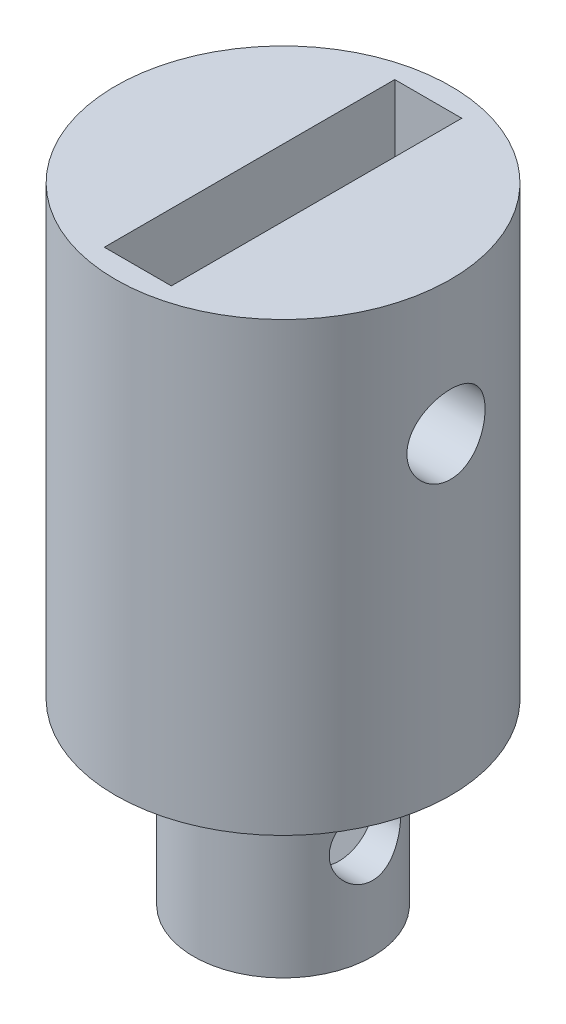
SolidWorks part; units mm, degrees
ref_plane "Front Plane" through (0, 0, 0) normal (0, 0, 1) x (1, 0, 0)
ref_plane "Top Plane" through (0, 0, 0) normal (0, 1, 0) x (1, 0, 0)
ref_plane "Right Plane" through (0, 0, 0) normal (1, 0, 0) x (0, 0, -1)
sketch "Sketch1" plane through (0, 0, 0) normal (0, 1, 0) x (1, 0, 0)
  circle A0 centre (0, 0) radius 7.5
  dimension "D1" = 15
extrude "Boss-Extrude1" add sketch "Sketch1" along normal blind 20
sketch "Sketch2" plane through (0, 20, 0) normal (0, 1, 0) x (1, 0, 0)
  line L1 (-1.5, 6.5) -> (1.5, 6.5)
  line L2 (-1.5, 6.5) -> (-1.5, -6.5)
  line L3 (-1.5, -6.5) -> (1.5, -6.5)
  line L4 (1.5, 6.5) -> (1.5, -6.5)
  point P7 (-1.5, 0)
  point P9 (0, 6.5)
  dimension "D1" = 3
  dimension "D2" = 13
extrude "Cut-Extrude1" cut sketch "Sketch2" against normal blind 10
ref_plane "Plane1" through (7.5, 0, 0) normal (1, 0, 0) x (0, 0, -1)
sketch "Sketch3" plane through (7.5, 0, 0) normal (1, 0, 0) x (0, 0, -1)
  line L0 (0, 20) -> (0, 0) construction
  line L1 (-6.5, 20) -> (6.5, 20) construction
  line L3 (7.5, 20) -> (-7.5, 20) construction
  circle A0 centre (0, 14) radius 1.75
  dimension "D1" = 3.5
  dimension "D2" = 6
extrude "Cut-Extrude2" cut sketch "Sketch3" against normal through all
sketch "Sketch4" plane through (0, 0, 0) normal (0, -1, 0) x (1, 0, 0)
  circle A0 centre (0, 0) radius 4
  dimension "D1" = 8
extrude "Boss-Extrude2" add sketch "Sketch4" along normal blind 8
sketch "Sketch5" plane through (0, -8, 0) normal (0, -1, 0) x (1, 0, 0)
  line L1 (2.5, -2) -> (-2.5, -2)
  line L2 (2.5, -2) -> (2.5, 2)
  line L3 (2.5, 2) -> (-2.5, 2)
  line L4 (-2.5, -2) -> (-2.5, 2)
  point P6 (0, -2)
  point P7 (2.5, 0)
  dimension "D1" = 5
  dimension "D2" = 4
extrude "Cut-Extrude3" cut sketch "Sketch5" against normal blind 6.2
sketch "Sketch6" plane through (7.5, 0, 0) normal (1, 0, 0) x (0, 0, -1)
  line L0 (2, -1.8) -> (-2, -1.8) construction
  circle A0 centre (0, -3.45) radius 1.6
  dimension "D1" = 3.2
  dimension "D2" = 1.65
extrude "Cut-Extrude4" cut sketch "Sketch6" against normal through all
